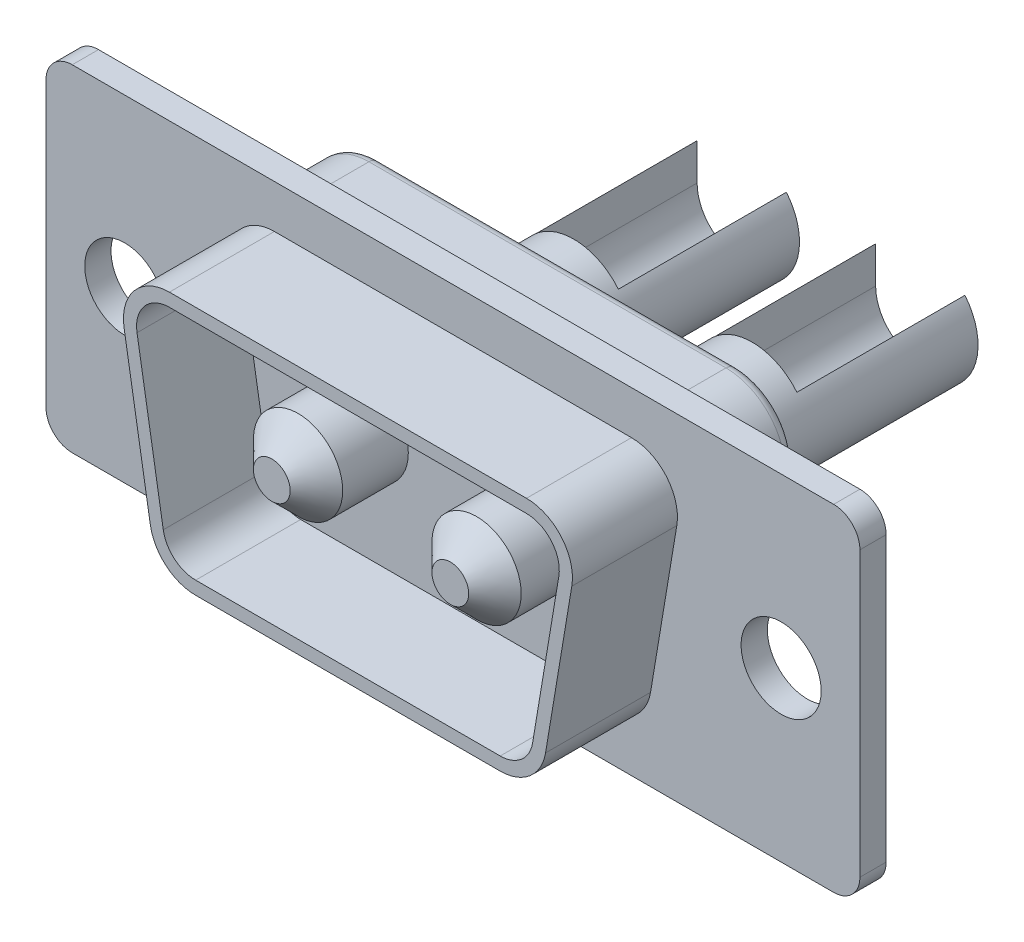
SolidWorks part; units mm, degrees
ref_plane "Top Plane" through (0, 0, 0) normal (0, 0, 1) x (1, 0, 0)
ref_plane "Right Plane" through (0, 0, 0) normal (0, 1, 0) x (1, 0, 0)
ref_plane "Front Plane" through (0, 0, 0) normal (1, 0, 0) x (0, 0, -1)
sketch "Sketch1" plane through (0, 0, 0) normal (0, 0, 1) x (1, 0, 0)
  line L0 (-15.5, 6.4) -> (15.5, -6.4) construction
  line L1 (-15.5, 6.4) -> (15.5, 6.4)
  line L2 (-15.5, 6.4) -> (-15.5, -6.4)
  line L3 (-15.5, -6.4) -> (15.5, -6.4)
  line L4 (15.5, 6.4) -> (15.5, -6.4)
  line L5 (0, 6.4) -> (0, -6.4) construction
  circle A0 centre (-12.5, 0) radius 1.525 construction
  circle A1 centre (12.5, 0) radius 1.525 construction
  dimension "D3" = 25
  dimension "D4" = 3.05
  dimension "D1" = 31
  dimension "D2" = 12.8
extrude "Boss-Extrude1" add sketch "Sketch1" along normal mid plane 1
sketch "Sketch2" plane through (0, 0, 0.5) normal (0, 0, 1) x (1, 0, 0)
  circle A0 centre (12.5, 0) radius 1.525 construction
  circle A1 centre (-12.5, 0) radius 1.525 construction
  circle A2 centre (12.5, 0) radius 1.525
  circle A3 centre (-12.5, 0) radius 1.525
extrude "Cut-Extrude1" cut sketch "Sketch2" against normal through all
sketch "Sketch3" plane through (0, 0, 0.5) normal (0, 0, 1) x (1, 0, 0)
  line L0 (0, -4.25) -> (0, 4.25) construction
  line L1 (-7.033, -3.2055) -> (-8.033, 2.7945)
  line L2 (-5.8, -4.25) -> (5.8, -4.25)
  line L3 (7.033, -3.2055) -> (8.033, 2.7945)
  line L4 (-6.8, 4.25) -> (6.8, 4.25)
  line L5 (-7.5262, -3.2877) -> (-8.5262, 2.7123) construction
  line L6 (-6.8, 4.75) -> (6.8, 4.75) construction
  line L7 (7.5262, -3.2877) -> (8.5262, 2.7123) construction
  line L8 (-5.8, -4.75) -> (5.8, -4.75) construction
  arc A0 (-6.8, 4.25) -> (-8.033, 2.7945) centre (-6.8, 3) ccw
  arc A1 (-7.033, -3.2055) -> (-5.8, -4.25) centre (-5.8, -3) ccw
  arc A2 (7.033, -3.2055) -> (5.8, -4.25) centre (5.8, -3) cw
  arc A3 (6.8, 4.25) -> (8.033, 2.7945) centre (6.8, 3) cw
  arc A4 (-6.8, 4.75) -> (-8.5262, 2.7123) centre (-6.8, 3) ccw construction
  arc A5 (6.8, 4.75) -> (8.5262, 2.7123) centre (6.8, 3) cw construction
  arc A6 (7.5262, -3.2877) -> (5.8, -4.75) centre (5.8, -3) cw construction
  arc A7 (-7.5262, -3.2877) -> (-5.8, -4.75) centre (-5.8, -3) ccw construction
  point P13 (-8.05, 3)
  point P18 (8.05, 3)
  dimension "D1" = 2.5
  dimension "D2" = 16.1
  dimension "D3" = 1
  dimension "D4" = 8.5
  dimension "D5" = 0.5
extrude "Boss-Extrude2" [suppressed] add sketch "Sketch3" along normal blind 4
sketch "Sketch10" plane through (0, 0, 0.5) normal (0, 0, 1) x (1, 0, 0)
  line L0 (-7.033, -3.2055) -> (-8.033, 2.7945) construction
  line L1 (-5.8, -4.25) -> (5.8, -4.25) construction
  line L2 (7.033, -3.2055) -> (8.033, 2.7945) construction
  line L3 (-6.8, 4.25) -> (6.8, 4.25) construction
  line L4 (-7.033, -3.2055) -> (-8.033, 2.7945)
  line L5 (-5.8, -4.25) -> (5.8, -4.25)
  line L6 (7.033, -3.2055) -> (8.033, 2.7945)
  line L7 (-6.8, 4.25) -> (6.8, 4.25)
  line L8 (-7.5262, -3.2877) -> (-8.5262, 2.7123) construction
  line L9 (-5.8, -4.75) -> (5.8, -4.75) construction
  line L10 (7.5262, -3.2877) -> (8.5262, 2.7123) construction
  line L11 (-6.8, 4.75) -> (6.8, 4.75) construction
  line L12 (-7.5262, -3.2877) -> (-8.5262, 2.7123)
  line L13 (-5.8, -4.75) -> (5.8, -4.75)
  line L14 (7.5262, -3.2877) -> (8.5262, 2.7123)
  line L15 (-6.8, 4.75) -> (6.8, 4.75)
  arc A0 (-6.8, 4.25) -> (-8.033, 2.7945) centre (-6.8, 3) ccw construction
  arc A1 (-7.033, -3.2055) -> (-5.8, -4.25) centre (-5.8, -3) ccw construction
  arc A2 (5.8, -4.25) -> (7.033, -3.2055) centre (5.8, -3) ccw construction
  arc A3 (8.033, 2.7945) -> (6.8, 4.25) centre (6.8, 3) ccw construction
  arc A4 (-6.8, 4.25) -> (-8.033, 2.7945) centre (-6.8, 3) ccw
  arc A5 (-7.033, -3.2055) -> (-5.8, -4.25) centre (-5.8, -3) ccw
  arc A6 (5.8, -4.25) -> (7.033, -3.2055) centre (5.8, -3) ccw
  arc A7 (8.033, 2.7945) -> (6.8, 4.25) centre (6.8, 3) ccw
  arc A8 (-6.8, 4.75) -> (-8.5262, 2.7123) centre (-6.8, 3) ccw construction
  arc A9 (-7.5262, -3.2877) -> (-5.8, -4.75) centre (-5.8, -3) ccw construction
  arc A10 (5.8, -4.75) -> (7.5262, -3.2877) centre (5.8, -3) ccw construction
  arc A11 (8.5262, 2.7123) -> (6.8, 4.75) centre (6.8, 3) ccw construction
  arc A12 (-6.8, 4.75) -> (-8.5262, 2.7123) centre (-6.8, 3) ccw
  arc A13 (-7.5262, -3.2877) -> (-5.8, -4.75) centre (-5.8, -3) ccw
  arc A14 (5.8, -4.75) -> (7.5262, -3.2877) centre (5.8, -3) ccw
  arc A15 (8.5262, 2.7123) -> (6.8, 4.75) centre (6.8, 3) ccw
extrude "Boss-Extrude5" add sketch "Sketch10" along normal blind 4
sketch "Sketch5" plane through (0, 0, -0.5) normal (0, 0, -1) x (-1, 0, 0)
  line L8 (8.0194, -3.3699) -> (9.0194, 2.6301)
  line L9 (-5.8, -5.25) -> (5.8, -5.25)
  line L10 (-9.0194, 2.6301) -> (-8.0194, -3.3699)
  line L11 (6.8, 5.25) -> (-6.8, 5.25)
  line L12 (8.0194, -3.3699) -> (9.0194, 2.6301)
  line L13 (-5.8, -5.25) -> (5.8, -5.25)
  line L14 (-9.0194, 2.6301) -> (-8.0194, -3.3699)
  line L15 (6.8, 5.25) -> (-6.8, 5.25)
  arc A8 (9.0194, 2.6301) -> (6.8, 5.25) centre (6.8, 3) ccw
  arc A9 (5.8, -5.25) -> (8.0194, -3.3699) centre (5.8, -3) ccw
  arc A10 (-8.0194, -3.3699) -> (-5.8, -5.25) centre (-5.8, -3) ccw
  arc A11 (-6.8, 5.25) -> (-9.0194, 2.6301) centre (-6.8, 3) ccw
  arc A12 (9.0194, 2.6301) -> (6.8, 5.25) centre (6.8, 3) ccw
  arc A13 (5.8, -5.25) -> (8.0194, -3.3699) centre (5.8, -3) ccw
  arc A14 (-8.0194, -3.3699) -> (-5.8, -5.25) centre (-5.8, -3) ccw
  arc A15 (-6.8, 5.25) -> (-9.0194, 2.6301) centre (-6.8, 3) ccw
  dimension "D1" = 0.5
extrude "Boss-Extrude3" add sketch "Sketch5" along normal blind 3
sketch "Sketch6" plane through (0, 0, -3.5) normal (0, 0, -1) x (-1, 0, 0)
  line L0 (0, 6.1668) -> (0, -6.0028) construction
  circle A0 centre (-3.4, 0) radius 2.2
  circle A1 centre (3.4, 0) radius 2.2
  dimension "D1" = 6.8
  dimension "D2" = 4.4
extrude "Boss-Extrude4" add sketch "Sketch6" along normal blind 10.4
sketch "Sketch7" plane through (0, 0, -13.9) normal (0, 0, -1) x (-1, 0, 0)
  line L0 (-5.1, 0) -> (-5.1, 1.3964)
  line L1 (-1.7, 0) -> (-1.7, 1.3964)
  line L2 (0, 4.25) -> (0, -4.25) construction
  line L3 (1.7, 0) -> (1.7, 1.3964)
  line L4 (5.1, 0) -> (5.1, 1.3964)
  circle A8 centre (-3.4, 0) radius 1.7
  arc A9 (-5.1, 0) -> (-1.7, 0) centre (-3.4, 0) ccw
  circle A10 centre (-3.4, 0) radius 2.2 construction
  arc A11 (1.7, 1.3964) -> (5.1, 1.3964) centre (3.4, 0) cw
  arc A12 (5.1, 0) -> (1.7, 0) centre (3.4, 0) cw
  arc A13 (-1.7, 1.3964) -> (-5.1, 1.3964) centre (-3.4, 0) ccw
  dimension "D1" = 0.5
extrude "Cut-Extrude2" cut sketch "Sketch7" against normal offset from surface (6.4 mm away) 4 up to face at (-1.2, 0, -3.5)
sketch "Sketch9" [suppressed] plane through (0, 0, 4.5) normal (0, 0, 1) x (1, 0, 0)
  arc A0 (-5.1, 0) -> (-1.7, 0) centre (-3.4, 0) ccw construction
  circle A1 centre (-3.4, 0) radius 1.7
  arc A2 (1.7, 0) -> (5.1, 0) centre (3.4, 0) ccw construction
  circle A3 centre (3.4, 0) radius 1.7
extrude "Cut-Extrude3" [suppressed] cut sketch "Sketch9" against normal blind 4
sketch "Sketch12" plane through (0, 0, 0.5) normal (0, 0, 1) x (1, 0, 0)
  arc A0 (-5.1, 0) -> (-1.7, 0) centre (-3.4, 0) ccw construction
  circle A1 centre (-3.4, 0) radius 1.7
  arc A2 (1.7, 0) -> (5.1, 0) centre (3.4, 0) ccw construction
  circle A3 centre (3.4, 0) radius 1.7
  point P6 (-1.7, 0.1808)
  point P8 (5.1, 0.3143)
extrude "Boss-Extrude6" add sketch "Sketch12" along normal blind 3.5
chamfer "Chamfer1" distance 1 angle 45 2 edges at (5.1, 0, 4) (-1.7, 0, 4)
fillet "Fillet1" radius 1 4 edges at (15.5, 6.4, 0) (15.5, -6.4, 0) (-15.5, -6.4, 0) (-15.5, 6.4, 0)
fillet "Fillet2" radius 0.4 8 edges at (-8.5168, 4.4543, -3.5) (-8.5194, -0.3699, -3.5) (-7.2543, -4.7168, -3.5) (0, -5.25, -3.5) (7.2543, -4.7168, -3.5) (8.5194, -0.3699, -3.5) (8.5168, 4.4543, -3.5) (0, 5.25, -3.5)
fillet "Fillet4" [suppressed] radius 0.4
